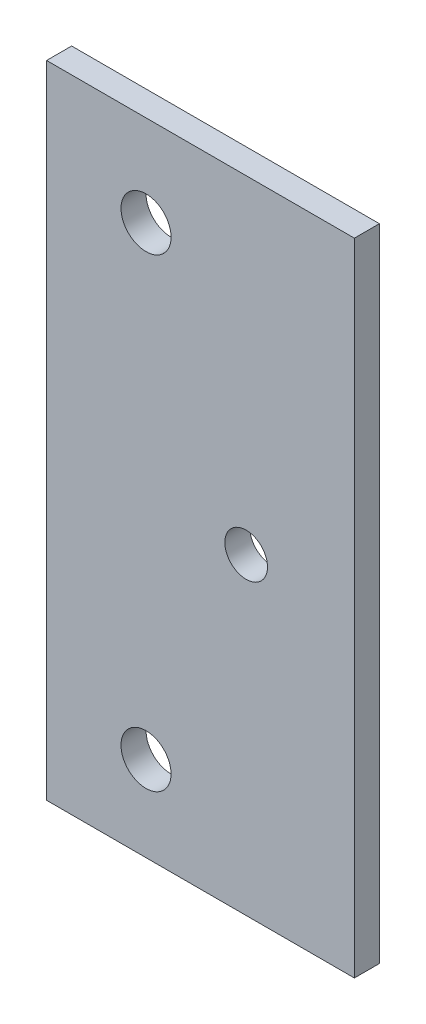
SolidWorks part; units mm, degrees
ref_plane "Front Plane" through (0, 0, 0) normal (0, 0, 1) x (1, 0, 0)
ref_plane "Top Plane" through (0, 0, 0) normal (0, 1, 0) x (1, 0, 0)
ref_plane "Right Plane" through (0, 0, 0) normal (1, 0, 0) x (0, 0, -1)
sketch "Sketch1" plane through (0, 0, 0) normal (0, 0, 1) x (1, 0, 0)
  line L1 (-88.8102, 247.3725) -> (-49.7778, 247.3725)
  line L2 (-88.8102, 247.3725) -> (-88.8102, 166.1132)
  line L3 (-88.8102, 166.1132) -> (-49.7778, 166.1132)
  line L4 (-49.7778, 247.3725) -> (-49.7778, 166.1132)
  circle A0 centre (-76.2, 235.8571) radius 3.175
  circle A1 centre (-76.2, 176.8929) radius 3.175
  dimension "D1" = 6.35
  dimension "D2" = 6.35
  dimension "D3" = 81.2593
  dimension "D4" = 39.0323
  dimension "D5" = 11.5153
  dimension "D6" = 12.6102
extrude "Boss-Extrude1" add sketch "Sketch1" along normal blind 3.175
hole_wizard "1/4-28 Tapped Hole1" positions "Sketch4" profile "Sketch3" tap size "1/4-28" standard "ANSI Inch" end condition through all
sketch "Sketch4" plane through (0, 0, 3.175) normal (0, 0, 1) x (1, 0, 0)
  point P0 (-63.5, 205.74)
sketch "Sketch3" plane through (-63.5, 205.74, 3.175) normal (1, 0, 0) x (0, -1, 0)
  line L0 (0, 0) -> (0, 3.175)
  line L1 (0, 3.175) -> (2.7051, 3.175)
  line L2 (2.7051, 3.175) -> (2.7051, 0)
  line L5 (2.7051, 0) -> (0, 0)
  line L11 (0, -6.35) -> (0, 107.95) construction
  dimension "Thru Tap Drill Dia." = 5.4102
  dimension "Thru Tap Drill Depth" = 3.175
